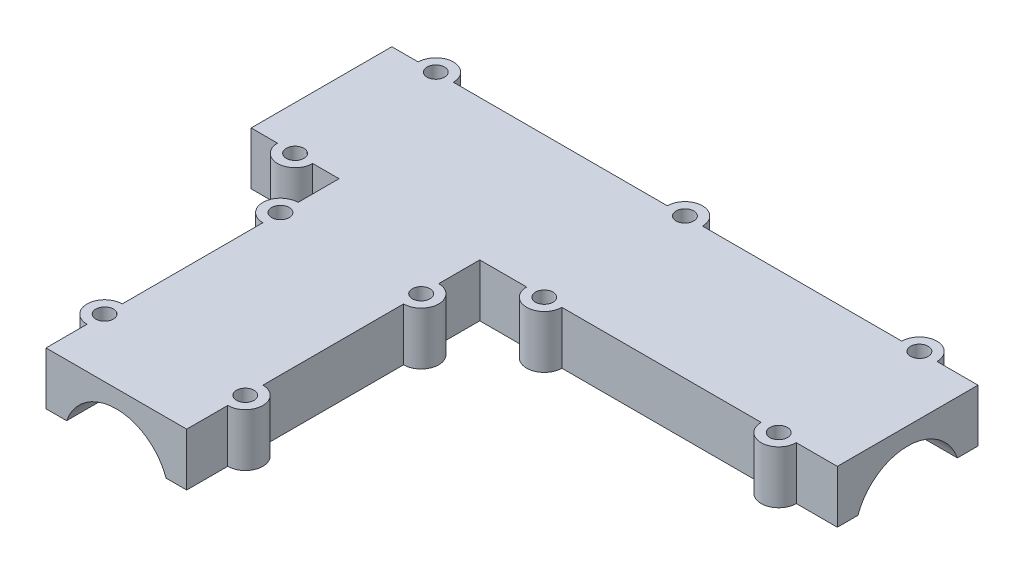
SolidWorks part; units mm, degrees
ref_plane "Front Plane" through (0, 0, 0) normal (0, 0, 1) x (1, 0, 0)
ref_plane "Top Plane" through (0, 0, 0) normal (0, 1, 0) x (1, 0, 0)
ref_plane "Right Plane" through (0, 0, 0) normal (1, 0, 0) x (0, 0, -1)
sketch "Sketch1" plane through (0, 0, 0) normal (1, 0, 0) x (0, 0, -1)
  line L1 (0, 0) -> (24, 0)
  line L2 (0, 0) -> (0, 24)
  line L3 (0, 24) -> (24, 24)
  line L4 (24, 0) -> (24, 24)
  dimension "D1" = 24
  dimension "D2" = 24
extrude "Boss-Extrude1" add sketch "Sketch1" along normal blind 100
sketch "Sketch2" plane through (100, 0, 0) normal (1, 0, 0) x (0, 0, -1)
  line L0 (0, 24) -> (0, 0) construction
  line L2 (0, 0) -> (24, 0) construction
  circle A0 centre (12, 12) radius 9
  point P4 (0, 0)
  point P6 (14.2054, 0)
  dimension "D1" = 18
  dimension "D2" = 12
  dimension "D3" = 12
extrude "Cut-Extrude1" cut sketch "Sketch2" against normal blind 100
sketch "Sketch3" plane through (0, 0, 0) normal (0, 0, 1) x (1, 0, 0)
  line L0 (100, 24) -> (0, 24) construction
  line L1 (15, 24) -> (39, 24)
  line L2 (15, 24) -> (15, 0)
  line L3 (15, 0) -> (39, 0)
  line L4 (39, 24) -> (39, 0)
  line L5 (100, 0) -> (0, 0) construction
  line L6 (0, 24) -> (0, 0) construction
  dimension "D1" = 24
  dimension "D2" = 15
extrude "Boss-Extrude2" add sketch "Sketch3" along normal blind 50
sketch "Sketch4" plane through (0, 0, 50) normal (0, 0, 1) x (1, 0, 0)
  line L0 (15, 24) -> (15, 0) construction
  line L2 (39, 24) -> (15, 24) construction
  circle A0 centre (27, 12) radius 9
  point P6 (29.0403, 24)
  dimension "D1" = 18
  dimension "D2" = 12
  dimension "D3" = 12
extrude "Cut-Extrude2" cut sketch "Sketch4" against normal blind 50
sketch "Sketch5" plane through (0, 24, 0) normal (0, 1, 0) x (1, 0, 0)
  line L0 (100, 0) -> (39, 0) construction
  line L1 (100, 24) -> (0, 24) construction
  line L2 (15, 0) -> (0, 0) construction
  line L3 (15, -50) -> (15, 0) construction
  line L4 (39, -50) -> (39, 0) construction
  line L5 (100, 24) -> (100, 0) construction
  circle A0 centre (90, 0) radius 3
  circle A1 centre (90, 24) radius 3
  circle A2 centre (50, 0) radius 3
  circle A3 centre (50, 24) radius 3
  circle A4 centre (7.5, 0) radius 3
  circle A5 centre (7.5, 24) radius 3
  circle A6 centre (15, -10) radius 3
  circle A7 centre (39, -10) radius 3
  circle A8 centre (15, -40) radius 3
  circle A9 centre (39, -40) radius 3
  point P32 (14.0822, -40.8433)
  dimension "D1" = 6
  dimension "D2" = 6
  dimension "D3" = 6
  dimension "D4" = 6
  dimension "D5" = 6
  dimension "D6" = 6
  dimension "D7" = 6
  dimension "D8" = 6
  dimension "D9" = 6
  dimension "D10" = 6
  dimension "D11" = 30
  dimension "D12" = 10
  dimension "D13" = 30
  dimension "D14" = 10
  dimension "D15" = 7.5
  dimension "D16" = 7.5
  dimension "D17" = 40
  dimension "D18" = 40
  dimension "D19" = 10
  dimension "D20" = 10
extrude "Boss-Extrude3" add sketch "Sketch5" against normal blind 24
sketch "Sketch6" plane through (0, 24, 0) normal (0, 1, 0) x (1, 0, 0)
  circle A2 centre (50, 24) radius 1.5
  circle A3 centre (50, 0) radius 1.5
  circle A4 centre (90, 24) radius 1.5
  circle A5 centre (90, 0) radius 1.5
  circle A6 centre (15, -40) radius 1.5
  circle A7 centre (15, -10) radius 1.5
  circle A8 centre (39, -10) radius 1.5
  circle A9 centre (39, -40) radius 1.5
  circle A10 centre (7.5, 0) radius 1.5
  circle A11 centre (7.5, 24) radius 1.5
  dimension "D1" = 3
  dimension "D2" = 3
  dimension "D3" = 3
  dimension "D4" = 3
  dimension "D5" = 3
  dimension "D6" = 3
  dimension "D7" = 3
  dimension "D8" = 3
  dimension "D9" = 3
  dimension "D10" = 3
extrude "Cut-Extrude3" cut sketch "Sketch6" against normal blind 24
sketch "Sketch7" plane through (100, 0, 0) normal (1, 0, 0) x (0, 0, -1)
  line L0 (27, 0) -> (27, 24) construction
  line L1 (27, 0) -> (-50, 0)
  line L2 (27, 0) -> (27, 15)
  line L3 (27, 15) -> (-50, 15)
  line L4 (-50, 0) -> (-50, 15)
  line L5 (-50, 0) -> (-50, 24) construction
  dimension "D1" = 0
  dimension "D2" = 0
  dimension "D3" = 15
extrude "Cut-Extrude4" cut sketch "Sketch7" against normal through all both and the other way through all
